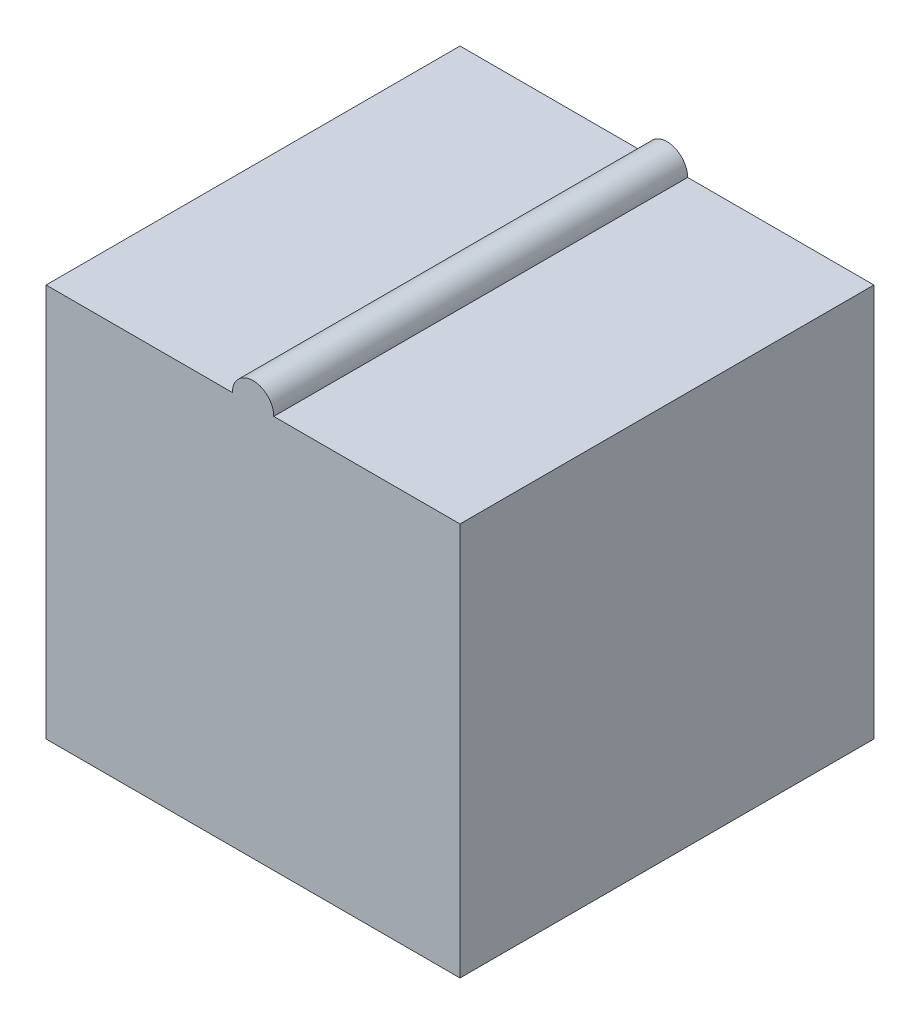
SolidWorks part; units mm, degrees
ref_plane "Front Plane" through (0, 0, 0) normal (0, 0, 1) x (1, 0, 0)
ref_plane "Top Plane" through (0, 0, 0) normal (0, 1, 0) x (1, 0, 0)
ref_plane "Right Plane" through (0, 0, 0) normal (1, 0, 0) x (0, 0, -1)
sketch "Sketch1" plane through (0, 0, 0) normal (0, 0, 1) x (1, 0, 0)
  line L0 (11, 19) -> (20, 19)
  line L1 (0, 0) -> (20, 0)
  line L2 (0, 0) -> (0, 19)
  line L3 (0, 19) -> (9, 19)
  line L4 (20, 0) -> (20, 19)
  line L5 (0, 19) -> (20, 19) construction
  arc A0 (11, 19) -> (9, 19) centre (10, 19) ccw
  dimension "D3" = 2
  dimension "D1" = 19
  dimension "D2" = 20
extrude "Boss-Extrude1" add sketch "Sketch1" along normal blind 20
